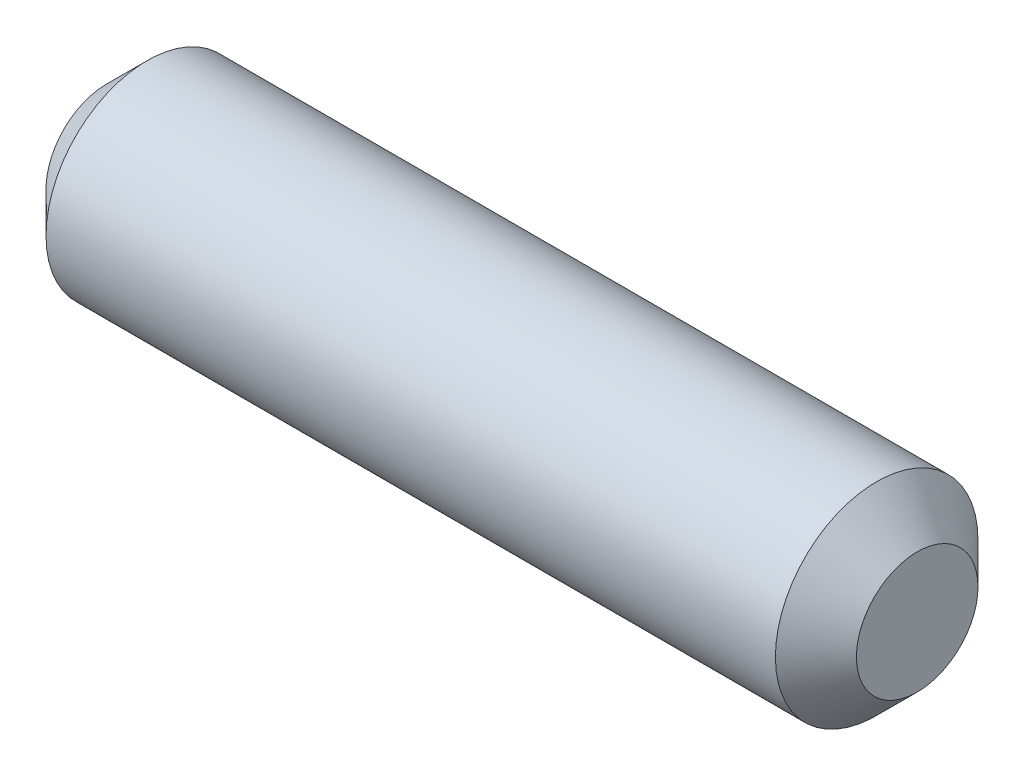
SolidWorks part; units mm, degrees
material "AISI 304"
ref_plane "Front Plane" through (0, 0, 0) normal (0, 0, 1) x (1, 0, 0)
ref_plane "Top Plane" through (0, 0, 0) normal (0, 1, 0) x (1, 0, 0)
ref_plane "Right Plane" through (0, 0, 0) normal (1, 0, 0) x (0, 0, -1)
sketch "Sketch1" plane through (0, 0, 0) normal (1, 0, 0) x (0, 0, -1)
  circle A0 centre (0, 0) radius 1.25
  dimension "D1" = 2.5
extrude "Boss-Extrude1" add sketch "Sketch1" along normal blind 10
chamfer "Chamfer1" distance 0.5 2 edges at (10, 0, -1.25) (0, 0, -1.25)
